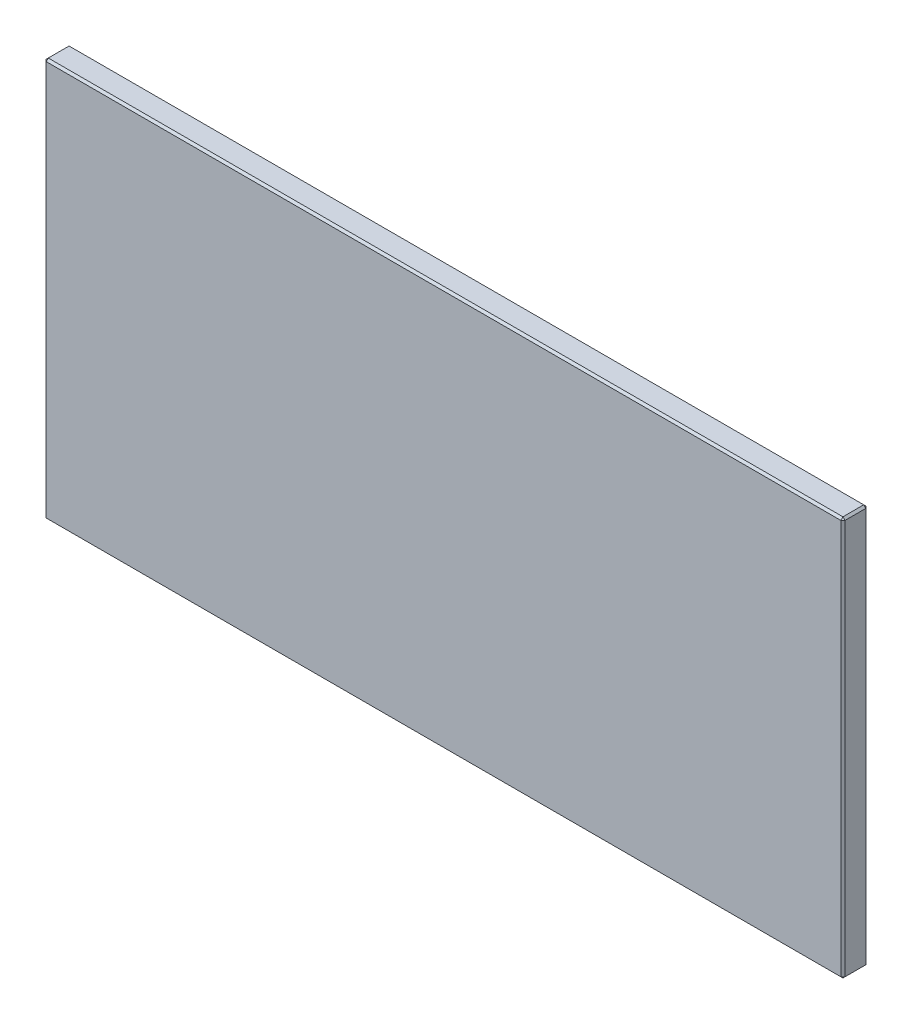
SolidWorks part; units mm, degrees
ref_plane "Plane1" through (0, 0, 0) normal (0, 0, 1) x (1, 0, 0)
ref_plane "Plane2" through (0, 0, 0) normal (0, 1, 0) x (1, 0, 0)
ref_plane "Plane3" through (0, 0, 0) normal (1, 0, 0) x (0, 0, -1)
sketch "Sketch1" plane through (0, 0, 0) normal (0, 0, 1) x (1, 0, 0)
  line L1 (-609.6, 304.8) -> (609.6, 304.8)
  line L2 (-609.6, 304.8) -> (-609.6, -304.8)
  line L3 (-609.6, -304.8) -> (609.6, -304.8)
  line L4 (609.6, 304.8) -> (609.6, -304.8)
  dimension "D1" = 1219.2
  dimension "D2" = 609.6
  dimension "D3" = 609.6
  dimension "D4" = 304.8
extrude "Base-Extrude" add sketch "Sketch1" along normal blind 38.1
chamfer "Chamfer1" distance 3.175 angle 45
